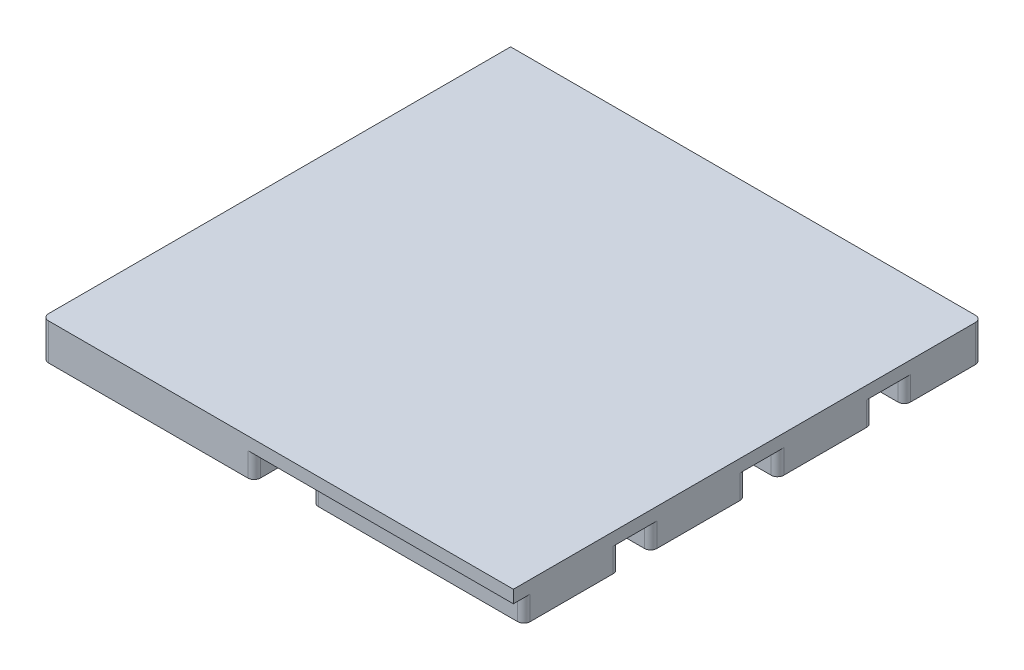
SolidWorks part; units mm, degrees
ref_plane "Front Plane" through (0, 0, 0) normal (0, 0, 1) x (1, 0, 0)
ref_plane "Top Plane" through (0, 0, 0) normal (0, 1, 0) x (1, 0, 0)
ref_plane "Right Plane" through (0, 0, 0) normal (1, 0, 0) x (0, 0, -1)
sketch "Sketch2" plane through (0, 0, 0) normal (0, 1, 0) x (1, 0, 0)
  line L1 (0, 0) -> (149, 0)
  line L2 (0, 0) -> (0, 148.13)
  line L3 (0, 148.13) -> (149, 148.13)
  line L4 (149, 0) -> (149, 148.13)
  dimension "D1" = 149
  dimension "D2" = 148.13
extrude "Boss-Extrude1" add sketch "Sketch2" along normal blind 4
sketch "Sketch3" plane through (0, 4, 0) normal (0, 1, 0) x (1, 0, 0)
  line L0 (0, 148.13) -> (0, 0) construction
  line L1 (149, 148.13) -> (82, 148.13)
  line L2 (149, 148.13) -> (149, 123.63)
  line L3 (149, 123.63) -> (82, 123.63)
  line L4 (82, 148.13) -> (82, 123.63)
  line L5 (0, 144.7967) -> (67, 144.7967)
  line L6 (0, 144.7967) -> (0, 120.2967)
  line L7 (0, 120.2967) -> (67, 120.2967)
  line L8 (67, 144.7967) -> (67, 120.2967)
  line L9 (149, 148.13) -> (0, 148.13) construction
  line L10 (149, 0) -> (149, 148.13) construction
  line L11 (149, 113.73) -> (82, 113.73)
  line L12 (149, 113.73) -> (149, 83.53)
  line L13 (149, 83.53) -> (82, 83.53)
  line L14 (82, 113.73) -> (82, 83.53)
  line L15 (97.3, 113.73) -> (97.3, 99.43) construction
  line L16 (0, 110.3967) -> (67, 110.3967)
  line L17 (0, 110.3967) -> (0, 80.1967)
  line L18 (0, 80.1967) -> (67, 80.1967)
  line L19 (67, 110.3967) -> (67, 80.1967)
  line L20 (149, 73.63) -> (82, 73.63)
  line L21 (149, 73.63) -> (149, 43.43)
  line L22 (149, 43.43) -> (82, 43.43)
  line L23 (82, 73.63) -> (82, 43.43)
  line L24 (0, 70.2967) -> (67, 70.2967)
  line L25 (0, 70.2967) -> (0, 40.0967)
  line L26 (0, 40.0967) -> (67, 40.0967)
  line L27 (67, 70.2967) -> (67, 40.0967)
  line L28 (0, 30.1967) -> (67, 30.1967)
  line L29 (0, 30.1967) -> (0, -0.0033)
  line L30 (0, -0.0033) -> (67, -0.0033)
  line L31 (67, 30.1967) -> (67, -0.0033)
  line L32 (97.3, 99.43) -> (97.3, 95.83) construction
  line L33 (149, 33.53) -> (82, 33.53)
  line L34 (149, 33.53) -> (149, 3.33)
  line L35 (149, 3.33) -> (82, 3.33)
  line L36 (82, 33.53) -> (82, 3.33)
  line L37 (12.85, 144.7967) -> (12.85, 137.4467) construction
  line L38 (12.85, 137.4467) -> (40.15, 137.4467)
  line L39 (12.85, 137.4467) -> (12.85, 133.7967) construction
  line L40 (12.85, 133.7967) -> (12.85, 120.2967) construction
  line L41 (12.85, 133.7967) -> (40.15, 133.7967)
  line L42 (97.3, 148.13) -> (97.3, 140.13) construction
  line L43 (97.3, 140.13) -> (97.3, 136.48) construction
  line L44 (97.3, 136.48) -> (97.3, 123.63) construction
  line L45 (97.3, 140.13) -> (124.6, 140.13)
  line L46 (97.3, 136.48) -> (124.6, 136.48)
  line L47 (0, 0) -> (149, 0) construction
  line L48 (97.3, 95.83) -> (97.3, 83.53) construction
  line L49 (97.3, 99.43) -> (124.6, 99.43)
  line L50 (97.3, 95.83) -> (124.6, 95.83)
  line L51 (12.85, 110.3967) -> (12.85, 96.0967) construction
  line L52 (12.85, 96.0967) -> (12.85, 92.4967) construction
  line L53 (12.85, 92.4967) -> (12.85, 80.1967) construction
  line L54 (12.85, 96.0967) -> (40.15, 96.0967)
  line L55 (12.85, 92.4967) -> (40.15, 92.4967)
  line L56 (12.85, 70.2967) -> (12.85, 55.9967) construction
  line L57 (12.85, 55.9967) -> (12.85, 52.3967) construction
  line L58 (12.85, 52.3967) -> (12.85, 40.0967) construction
  line L59 (12.85, 55.9967) -> (40.15, 55.9967)
  line L60 (12.85, 52.3967) -> (40.15, 52.3967)
  line L61 (97.3, 73.63) -> (97.3, 59.33) construction
  line L62 (97.3, 59.33) -> (97.3, 55.73) construction
  line L63 (97.3, 55.73) -> (97.3, 43.43) construction
  line L64 (97.3, 59.33) -> (124.6, 59.33)
  line L65 (97.3, 55.73) -> (124.6, 55.73)
  line L66 (12.85, 30.1967) -> (12.85, 15.8967) construction
  line L67 (12.85, 15.8967) -> (12.85, 12.2967) construction
  line L68 (12.85, 12.2967) -> (12.85, -0.0033) construction
  line L69 (12.85, 15.8967) -> (40.15, 15.8967)
  line L70 (12.85, 12.2967) -> (40.15, 12.2967)
  line L71 (97.3, 33.53) -> (97.3, 19.23) construction
  line L72 (97.3, 19.23) -> (97.3, 15.63) construction
  line L73 (97.3, 15.63) -> (97.3, 3.33) construction
  line L74 (97.3, 19.23) -> (124.6, 19.23)
  line L75 (97.3, 15.63) -> (124.6, 15.63)
  arc A0 (12.85, 133.7967) -> (12.85, 137.4467) centre (12.85, 135.6217) cw
  arc A2 (40.15, 137.4467) -> (40.15, 133.7967) centre (40.15, 135.6217) cw
  arc A3 (97.3, 136.48) -> (97.3, 140.13) centre (97.3, 138.305) cw
  arc A4 (124.6, 140.13) -> (124.6, 136.48) centre (124.6, 138.305) cw
  arc A5 (97.3, 95.83) -> (97.3, 99.43) centre (97.3, 97.63) cw
  arc A6 (124.6, 99.43) -> (124.6, 95.83) centre (124.6, 97.63) cw
  arc A7 (12.85, 92.4967) -> (12.85, 96.0967) centre (12.85, 94.2967) cw
  arc A9 (40.15, 92.4967) -> (40.15, 96.0967) centre (40.15, 94.2967) ccw
  arc A10 (12.85, 52.3967) -> (12.85, 55.9967) centre (12.85, 54.1967) cw
  arc A11 (40.15, 55.9967) -> (40.15, 52.3967) centre (40.15, 54.1967) cw
  arc A12 (97.3, 55.73) -> (97.3, 59.33) centre (97.3, 57.53) cw
  arc A13 (124.6, 59.33) -> (124.6, 55.73) centre (124.6, 57.53) cw
  arc A14 (12.85, 12.2967) -> (12.85, 15.8967) centre (12.85, 14.0967) cw
  arc A15 (40.15, 15.8967) -> (40.15, 12.2967) centre (40.15, 14.0967) cw
  arc A16 (97.3, 15.63) -> (97.3, 19.23) centre (97.3, 17.43) cw
  arc A17 (124.6, 19.23) -> (124.6, 15.63) centre (124.6, 17.43) cw
  line M24 (0, 148.13) -> (0, 0)
  line M25 (0, 0) -> (149, 0)
  line M26 (149, 0) -> (149, 148.13)
  line M27 (149, 148.13) -> (0, 148.13)
  dimension "D31" = 24.4
  dimension "D1" = 67
  dimension "D2" = 24.5
  dimension "D3" = 3.3333
  dimension "D4" = 67
  dimension "D5" = 24.5
  dimension "D6" = 9.9
  dimension "D7" = 30.2
  dimension "D8" = 67
  dimension "D9" = 30.2
  dimension "D10" = 9.9
  dimension "D11" = 67
  dimension "D12" = 9.9
  dimension "D13" = 30.2
  dimension "D14" = 67
  dimension "D15" = 9.9
  dimension "D16" = 30.2
  dimension "D17" = 67
  dimension "D18" = 30.2
  dimension "D19" = 9.9
  dimension "D20" = 67
  dimension "D21" = 9.9
  dimension "D22" = 30.2
  dimension "D23" = 67
  dimension "D24" = 7.35
  dimension "D25" = 3.65
  dimension "D26" = 27.3
  dimension "D27" = 12.85
  dimension "D28" = 8
  dimension "D29" = 3.65
  dimension "D30" = 27.3
  dimension "D32" = 14.3
  dimension "D33" = 12.3
  dimension "D34" = 27.3
  dimension "D35" = 14.3
  dimension "D36" = 12.3
  dimension "D37" = 27.3
  dimension "D38" = 14.3
  dimension "D39" = 12.3
  dimension "D40" = 14.3
  dimension "D41" = 12.3
  dimension "D42" = 14.3
  dimension "D43" = 12.3
  dimension "D44" = 14.3
  dimension "D45" = 12.3
extrude "Boss-Extrude3" add sketch "Sketch3" against normal blind 11.55 contours L8 L5 L7 L38 A2 L41 A0 M24 | L4 L3 L45 A4 L46 A3 M27 M26 | L19 L16 L18 A9 L55 A7 L54 M24 | L11 L14 L13 L49 A6 L50 A5 M26 | L27 L24 L26 L59 A11 L60 A10 M24 | L20 L23 L22 L64 A13 L65 A12 M26 | L31 L28 L69 A15 L70 A14 M24 M25 | L33 L36 L35 L74 A17 L75 A16 M26
fillet "Fillet1" radius 2 32 edges at (82, -3.775, -3.33) (149, -3.775, -3.33) (82, -3.775, -33.53) (149, -3.775, -33.53) (67, -3.775, 0) (0, -1.775, 0) (67, -3.775, -30.1967) (0, -3.775, -30.1967) (67, -3.775, -40.0967) (0, -3.775, -40.0967) (82, -3.775, -43.43) (149, -3.775, -43.43) (82, -3.775, -73.63) (67, -3.775, -70.2967) (0, -3.775, -70.2967) (67, -3.775, -80.1967) (0, -3.775, -80.1967) (82, -3.775, -83.53) (67, -3.775, -110.3967) (0, -3.775, -110.3967) (149, -3.775, -83.53) (149, -3.775, -73.63) (82, -3.775, -113.73) (149, -3.775, -113.73) (67, -3.775, -120.2967) (0, -3.775, -120.2967) (67, -3.775, -144.7967) (0, -3.775, -144.7967) (82, -3.775, -123.63) (149, -3.775, -123.63) (149, -1.775, -148.13) (82, -3.775, -148.13)
